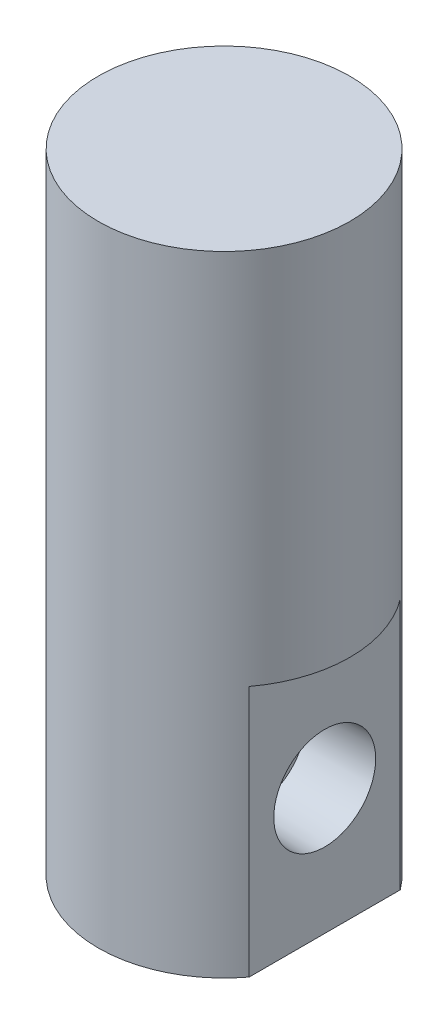
SolidWorks part; units mm, degrees
ref_plane "Front Plane" through (0, 0, 0) normal (0, 0, 1) x (1, 0, 0)
ref_plane "Top Plane" through (0, 0, 0) normal (0, 1, 0) x (1, 0, 0)
ref_plane "Right Plane" through (0, 0, 0) normal (1, 0, 0) x (0, 0, -1)
sketch "Sketch1" plane through (0, 0, 0) normal (0, 1, 0) x (1, 0, 0)
  circle A0 centre (0, 0) radius 12.7
  dimension "D1" = 25.4
extrude "Boss-Extrude1" add sketch "Sketch1" along normal blind 63.5
sketch "Sketch2" plane through (0, 0, 0) normal (0, -1, 0) x (1, 0, 0)
  line L0 (-10.16, 7.62) -> (-10.16, -7.62)
  line L1 (10.16, 7.62) -> (10.16, -7.62)
  circle A0 centre (0, 0) radius 12.7 construction
  arc A1 (-10.16, 7.62) -> (-10.16, -7.62) centre (0, 0) ccw
  arc A2 (10.16, -7.62) -> (10.16, 7.62) centre (0, 0) ccw
  dimension "D1" = 15.24
extrude "Cut-Extrude1" cut sketch "Sketch2" against normal blind 25.4
hole_wizard "1/8 NPT Tapped Hole1" positions "Sketch5" profile "Sketch4" size "1/8" standard "ANSI Inch"
sketch "Sketch5" plane through (-10.16, 0, 0) normal (-1, 0, 0) x (0, 0, 1)
  line L0 (7.62, 12.7) -> (-7.62, 12.7) construction
  line L1 (7.62, 25.4) -> (7.62, 0) construction
  line L2 (-7.62, 25.4) -> (-7.62, 0) construction
  line L4 (0, 0) -> (0, 25.4) construction
  line L5 (-7.62, 0) -> (7.62, 0) construction
  line L6 (-7.62, 25.4) -> (7.62, 25.4) construction
  point P0 (0, 12.7)
sketch "Sketch4" plane through (-10.16, 12.7, 0) normal (0, 1, 0) x (0, 0, 1)
  line L0 (0, 0) -> (0, 14.2175)
  line L1 (4.2164, 11.684) -> (0, 14.2175)
  line L2 (-4.2164, 11.684) -> (0, 14.2175) construction
  line L3 (4.2164, 11.684) -> (4.2164, 6.858)
  line L4 (4.2164, 6.858) -> (4.9362, 6.858)
  line L5 (4.9362, 6.858) -> (5.1415, 0)
  line L6 (-4.9362, 6.858) -> (-5.1415, 0) construction
  line L7 (5.1415, 0) -> (0, 0)
  line L8 (0, -6.35) -> (0, 107.95) construction
  line L11 (-4.2164, 6.858) -> (-4.9362, 6.858) construction
  dimension "Tap Drill Dia." = 8.4328
  dimension "Tap Drill Depth" = 11.684
  dimension "Thread Dia." = 10.283
  dimension "Thread Angle" = 3.43
  dimension "Thread Depth" = 6.858
  dimension "Drill Angle" = 118
mirror "Mirror1" about plane through (0, 0, 0) normal (1, 0, 0) of "1/8 NPT Tapped Hole1"
